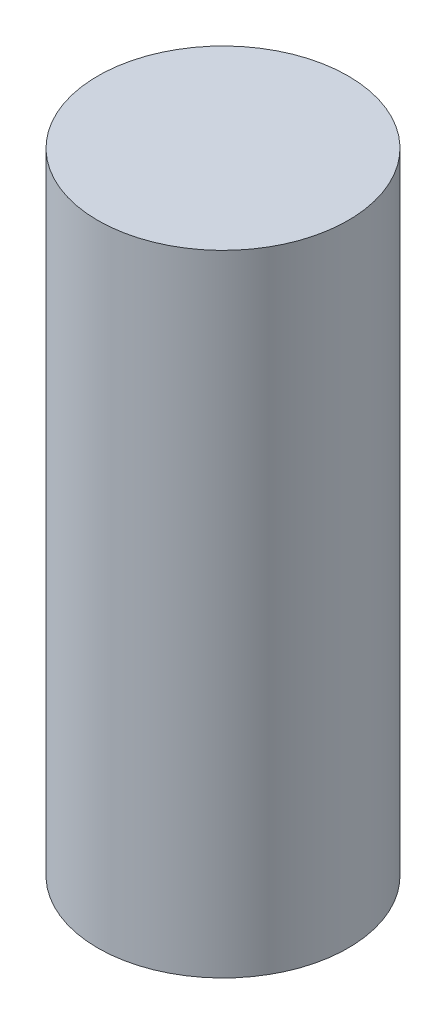
SolidWorks part; units mm, degrees
material "1.4000 (X6Cr13)"
ref_plane "Płaszczyzna przednia" through (0, 0, 0) normal (0, 0, 1) x (1, 0, 0)
ref_plane "Płaszczyzna górna" through (0, 0, 0) normal (0, 1, 0) x (1, 0, 0)
ref_plane "Płaszczyzna prawa" through (0, 0, 0) normal (1, 0, 0) x (0, 0, -1)
sketch "Szkic1" plane through (0, 0, 0) normal (0, 1, 0) x (1, 0, 0)
  circle A0 centre (0, 0) radius 2.225
  dimension "D1" = 4.45
extrude "Dodanie-wyciągnięcie1" add sketch "Szkic1" along normal blind 11.2
